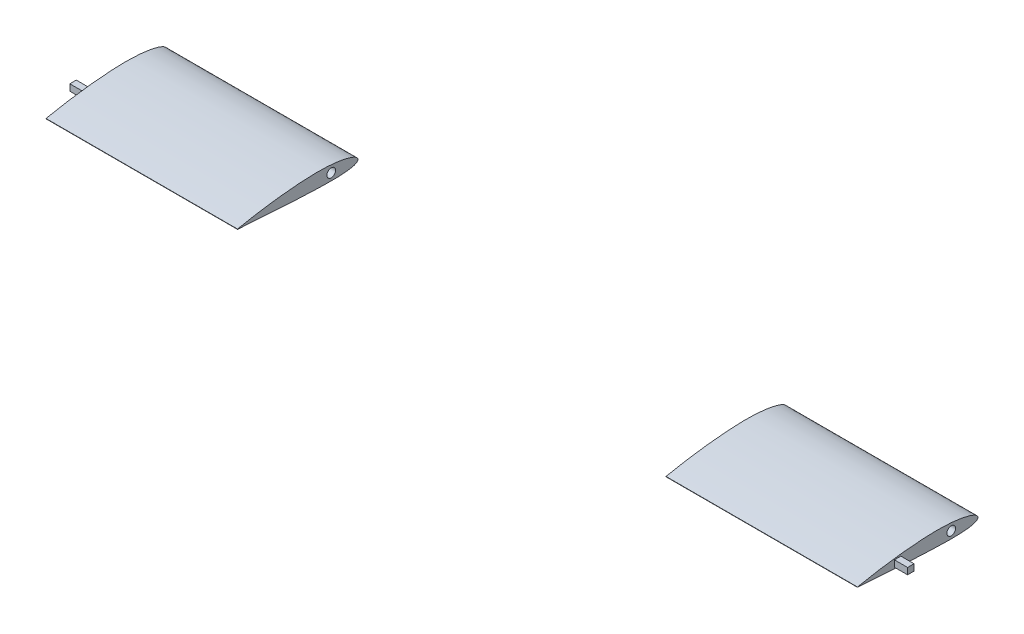
SolidWorks part; units mm, degrees
ref_plane "Front Plane" through (0, 0, 0) normal (0, 0, 1) x (1, 0, 0)
ref_plane "Top Plane" through (0, 0, 0) normal (0, 1, 0) x (1, 0, 0)
ref_plane "Right Plane" through (0, 0, 0) normal (1, 0, 0) x (0, 0, -1)
sketch "Sketch4" plane through (0, 0, 0) normal (0, 0, 1) x (1, 0, 0)
  line L0 (-30.3109, 17.5) -> (30.3109, 17.5)
  arc A1 (30.3109, 17.5) -> (-30.3109, 17.5) centre (0, 0) ccw
  dimension "D1" = 35
  dimension "D2" = 17.5
extrude "Exterior" add sketch "Sketch4" along normal blind 90 contours L0 A1
sketch "Sketch5" plane through (0, 0, 0) normal (0, 0, -1) x (-1, 0, 0)
  line L0 (30.3109, 17.5) -> (-30.3109, 17.5) construction
  line L1 (23.1247, 17.5) -> (-23.1247, 17.5)
  arc A0 (23.1247, 17.5) -> (-23.1247, 17.5) centre (0, 0) ccw
  dimension "D1" = 58
extrude "Boss-Extrude1" add sketch "Sketch5" along normal blind 15
curve "Curve3"
  spline degree 3 poles (0, 1.3, 1000) (0, 4.7133, 983.3426) (0, 11.531, 950.0715) (0, 24.0186, 883.4722) (0, 37.8548, 800.1781) (0, 52.175, 700.1592) (0, 64.1175, 600.1567) (0, 72.8619, 500.1109) (0, 78.7837, 400.0878) (0, 79.786, 316.6355) (0, 77.0249, 249.9395) (0, 72.979, 199.8766) (0, 66.5721, 149.7505) (0, 58.6825, 108.0331) (0, 49.7566, 74.7751) (0, 41.6416, 49.5609) (0, 32.1864, 28.1982) (0, 20.723, 9.771) (0, 0.8988, -6.2982) (0, -16.5264, 10.3934) (0, -24.4739, 28.476) (0, -30.5108, 49.7447) (0, -34.8393, 74.8759) (0, -38.5332, 108.2669) (0, -41.3764, 149.947) (0, -42.5163, 199.9941) (0, -42.3574, 250.0055) (0, -40.8857, 316.6783) (0, -38.2375, 400.0272) (0, -33.6287, 500.0334) (0, -27.6385, 600.0106) (0, -21.4122, 700.0048) (0, -15.1098, 800.0161) (0, -9.3053, 883.3314) (0, -4.8282, 950.0042) (0, -2.4761, 983.334) (0, -1.3, 1000) knots 0 0 0 0 0.025012 0.049959 0.099673 0.149206 0.198581 0.247805 0.296917 0.345953 0.370492 0.395091 0.419815 0.444799 0.45749 0.470406 0.483879 0.491264 0.503459 0.513609 0.520451 0.533235 0.545691 0.558032 0.582609 0.607135 0.631652 0.656174 0.705234 0.75432 0.803437 0.852566 0.901701 0.950849 0.975423 1 1 1 1
sketch "Sketch7" plane through (0, 0, 0) normal (1, 0, 0) x (0, 0, -1)
  line L0 (-90, 21.4324) -> (-90, 21.1984)
  line L1 (-90, 21.3154) -> (0, 21.434) construction
  line L2 (0, 21.434) -> (-0.0572, 64.8516) construction
  line L7 (-90, 17.5) -> (0, 17.5) construction
  line L9 (0, 17.5) -> (0, 29) construction
  spline S1 degree 3 poles (-90, 21.4324) (-88.5009, 21.7395) (-85.5067, 22.3531) (-79.5132, 23.4769) (-72.0173, 24.7221) (-63.0162, 26.0108) (-54.0165, 27.0856) (-45.013, 27.8725) (-36.0116, 28.4054) (-28.5014, 28.4956) (-22.4991, 28.2471) (-17.9938, 27.883) (-13.4827, 27.3065) (-9.7284, 26.5964) (-6.7354, 25.7932) (-4.4663, 25.0629) (-2.5438, 24.212) (-0.8854, 23.1803) (0.5607, 21.3963) (-0.9415, 19.8281) (-2.5688, 19.1129) (-4.4828, 18.5696) (-6.7445, 18.18) (-9.7495, 17.8476) (-13.5004, 17.5918) (-18.0044, 17.4892) (-22.5051, 17.5035) (-28.5052, 17.6359) (-36.0061, 17.8742) (-45.0061, 18.289) (-54.0034, 18.8281) (-63.0023, 19.3884) (-72.0027, 19.9556) (-79.5005, 20.478) (-85.5007, 20.8809) (-88.5002, 21.0925) (-90, 21.1984) knots 0 0 0 0 0.025012 0.049959 0.099673 0.149206 0.198581 0.247805 0.296917 0.345953 0.370492 0.395091 0.419815 0.444799 0.45749 0.470406 0.483879 0.491264 0.503459 0.513609 0.520451 0.533235 0.545691 0.558032 0.582609 0.607135 0.631652 0.656174 0.705234 0.75432 0.803437 0.852566 0.901701 0.950849 0.975423 1 1 1 1
  dimension "D1" = 90
ref_plane "Plane1" through (80, 0, 0) normal (1, 0, 0) x (0, 0, -1)
ref_plane "Plane2" through (-80, 0, 0) normal (1, 0, 0) x (0, 0, -1)
sketch "Sketch8" plane through (80, 0, 0) normal (1, 0, 0) x (0, 0, -1)
  line L0 (-90, 21.4324) -> (-90, 21.1984)
  spline S0 degree 3 poles (-716.115, 1915.3026) (-242.1094, -47.4437) (-166.1672, 7.229) (-79.5132, 23.4769) (-72.0173, 24.7221) (-63.0162, 26.0108) (-54.0165, 27.0856) (-45.013, 27.8725) (-36.0116, 28.4054) (-28.5014, 28.4956) (-22.4991, 28.2471) (-17.9938, 27.883) (-13.4827, 27.3065) (-9.7284, 26.5964) (-6.7354, 25.7932) (-4.4663, 25.0629) (-2.5438, 24.212) (-0.8854, 23.1803) (0.5607, 21.3963) (-0.9415, 19.8281) (-2.5688, 19.1129) (-4.4828, 18.5696) (-6.7445, 18.18) (-9.7495, 17.8476) (-13.5004, 17.5918) (-18.0044, 17.4892) (-22.5051, 17.5035) (-28.5052, 17.6359) (-36.0061, 17.8742) (-45.0061, 18.289) (-54.0034, 18.8281) (-63.0023, 19.3884) (-72.0027, 19.9556) (-79.5005, 20.478) (-222.3619, 30.0711) (-360.6967, 61.6518) (-633.8387, -1888.1939) knots -1.34139 -1.34139 -1.34139 -1.34139 0.025012 0.049959 0.099673 0.149206 0.198581 0.247805 0.296917 0.345953 0.370492 0.395091 0.419815 0.444799 0.45749 0.470406 0.483879 0.491264 0.503459 0.513609 0.520451 0.533235 0.545691 0.558032 0.582609 0.607135 0.631652 0.656174 0.705234 0.75432 0.803437 0.852566 0.901701 0.950849 0.975423 3.242166 3.242166 3.242166 3.242166 only from (-90, 21.4324) to (-90, 21.1984) construction
  spline S1 degree 3 poles (-90, 21.4324) (-88.5009, 21.7395) (-85.5067, 22.3531) (-79.5132, 23.4769) (-72.0173, 24.7221) (-63.0162, 26.0108) (-54.0165, 27.0856) (-45.013, 27.8725) (-36.0116, 28.4054) (-28.5014, 28.4956) (-22.4991, 28.2471) (-17.9938, 27.883) (-13.4827, 27.3065) (-9.7284, 26.5964) (-6.7354, 25.7932) (-4.4663, 25.0629) (-2.5438, 24.212) (-0.8854, 23.1803) (0.5607, 21.3963) (-0.9415, 19.8281) (-2.5688, 19.1129) (-4.4828, 18.5696) (-6.7445, 18.18) (-9.7495, 17.8476) (-13.5004, 17.5918) (-18.0044, 17.4892) (-22.5051, 17.5035) (-28.5052, 17.6359) (-36.0061, 17.8742) (-45.0061, 18.289) (-54.0034, 18.8281) (-63.0023, 19.3884) (-72.0027, 19.9556) (-79.5005, 20.478) (-85.5007, 20.8809) (-88.5002, 21.0925) (-90, 21.1984) knots 0 0 0 0 0.025012 0.049959 0.099673 0.149206 0.198581 0.247805 0.296917 0.345953 0.370492 0.395091 0.419815 0.444799 0.45749 0.470406 0.483879 0.491264 0.503459 0.513609 0.520451 0.533235 0.545691 0.558032 0.582609 0.607135 0.631652 0.656174 0.705234 0.75432 0.803437 0.852566 0.901701 0.950849 0.975423 1 1 1 1
sketch "Sketch9" plane through (-80, 0, 0) normal (1, 0, 0) x (0, 0, -1)
  line L0 (-90, 21.4324) -> (-90, 21.1984)
  spline S0 degree 3 poles (-716.115, 1915.3026) (-242.1094, -47.4437) (-166.1672, 7.229) (-79.5132, 23.4769) (-72.0173, 24.7221) (-63.0162, 26.0108) (-54.0165, 27.0856) (-45.013, 27.8725) (-36.0116, 28.4054) (-28.5014, 28.4956) (-22.4991, 28.2471) (-17.9938, 27.883) (-13.4827, 27.3065) (-9.7284, 26.5964) (-6.7354, 25.7932) (-4.4663, 25.0629) (-2.5438, 24.212) (-0.8854, 23.1803) (0.5607, 21.3963) (-0.9415, 19.8281) (-2.5688, 19.1129) (-4.4828, 18.5696) (-6.7445, 18.18) (-9.7495, 17.8476) (-13.5004, 17.5918) (-18.0044, 17.4892) (-22.5051, 17.5035) (-28.5052, 17.6359) (-36.0061, 17.8742) (-45.0061, 18.289) (-54.0034, 18.8281) (-63.0023, 19.3884) (-72.0027, 19.9556) (-79.5005, 20.478) (-222.3619, 30.0711) (-360.6967, 61.6518) (-633.8387, -1888.1939) knots -1.34139 -1.34139 -1.34139 -1.34139 0.025012 0.049959 0.099673 0.149206 0.198581 0.247805 0.296917 0.345953 0.370492 0.395091 0.419815 0.444799 0.45749 0.470406 0.483879 0.491264 0.503459 0.513609 0.520451 0.533235 0.545691 0.558032 0.582609 0.607135 0.631652 0.656174 0.705234 0.75432 0.803437 0.852566 0.901701 0.950849 0.975423 3.242166 3.242166 3.242166 3.242166 only from (-90, 21.4324) to (-90, 21.1984) construction
  spline S1 degree 3 poles (-90, 21.4324) (-88.5009, 21.7395) (-85.5067, 22.3531) (-79.5132, 23.4769) (-72.0173, 24.7221) (-63.0162, 26.0108) (-54.0165, 27.0856) (-45.013, 27.8725) (-36.0116, 28.4054) (-28.5014, 28.4956) (-22.4991, 28.2471) (-17.9938, 27.883) (-13.4827, 27.3065) (-9.7284, 26.5964) (-6.7354, 25.7932) (-4.4663, 25.0629) (-2.5438, 24.212) (-0.8854, 23.1803) (0.5607, 21.3963) (-0.9415, 19.8281) (-2.5688, 19.1129) (-4.4828, 18.5696) (-6.7445, 18.18) (-9.7495, 17.8476) (-13.5004, 17.5918) (-18.0044, 17.4892) (-22.5051, 17.5035) (-28.5052, 17.6359) (-36.0061, 17.8742) (-45.0061, 18.289) (-54.0034, 18.8281) (-63.0023, 19.3884) (-72.0027, 19.9556) (-79.5005, 20.478) (-85.5007, 20.8809) (-88.5002, 21.0925) (-90, 21.1984) knots 0 0 0 0 0.025012 0.049959 0.099673 0.149206 0.198581 0.247805 0.296917 0.345953 0.370492 0.395091 0.419815 0.444799 0.45749 0.470406 0.483879 0.491264 0.503459 0.513609 0.520451 0.533235 0.545691 0.558032 0.582609 0.607135 0.631652 0.656174 0.705234 0.75432 0.803437 0.852566 0.901701 0.950849 0.975423 1 1 1 1
loft "Loft9" add profiles "Sketch8", "Sketch9"
sketch "Sketch12" plane through (80, 0, 0) normal (1, 0, 0) x (0, 0, -1)
  line L0 (-90, 21.4324) -> (-90, 21.1984) construction
  line L1 (-90, 21.4324) -> (-90, 21.1984)
  line L2 (-90, 21.4324) -> (-97.2409, 26.9065)
  line L3 (-97.2409, 26.9065) -> (-90.2923, 42.7722)
  line L4 (-90.2923, 42.7722) -> (-30.1138, 44.0233)
  line L5 (-30.1138, 44.0233) -> (6.4186, 38.5184)
  line L6 (6.4186, 38.5184) -> (-0.0113, 30.0134)
  line L7 (0, 21.434) -> (-0.0572, 64.8516) construction
  line L8 (-0.0113, 30.0134) -> (-31.6288, 28.4362)
  spline S0 degree 3 poles (-716.115, 1915.3026) (-242.1094, -47.4437) (-166.1672, 7.229) (-79.5132, 23.4769) (-72.0173, 24.7221) (-63.0162, 26.0108) (-54.0165, 27.0856) (-45.013, 27.8725) (-36.0116, 28.4054) (-28.5014, 28.4956) (-22.4991, 28.2471) (-17.9938, 27.883) (-13.4827, 27.3065) (-9.7284, 26.5964) (-6.7354, 25.7932) (-4.4663, 25.0629) (-2.5438, 24.212) (-0.8854, 23.1803) (0.5607, 21.3963) (-0.9415, 19.8281) (-2.5688, 19.1129) (-4.4828, 18.5696) (-6.7445, 18.18) (-9.7495, 17.8476) (-13.5004, 17.5918) (-18.0044, 17.4892) (-22.5051, 17.5035) (-28.5052, 17.6359) (-36.0061, 17.8742) (-45.0061, 18.289) (-54.0034, 18.8281) (-63.0023, 19.3884) (-72.0027, 19.9556) (-79.5005, 20.478) (-222.3619, 30.0711) (-360.6967, 61.6518) (-633.8387, -1888.1939) knots -1.34139 -1.34139 -1.34139 -1.34139 0.025012 0.049959 0.099673 0.149206 0.198581 0.247805 0.296917 0.345953 0.370492 0.395091 0.419815 0.444799 0.45749 0.470406 0.483879 0.491264 0.503459 0.513609 0.520451 0.533235 0.545691 0.558032 0.582609 0.607135 0.631652 0.656174 0.705234 0.75432 0.803437 0.852566 0.901701 0.950849 0.975423 3.242166 3.242166 3.242166 3.242166 only from (-90, 21.4324) to (-90, 21.1984) construction
  spline S1 degree 3 poles (-90, 21.4324) (-88.5009, 21.7395) (-85.5067, 22.3531) (-79.5132, 23.4769) (-72.0173, 24.7221) (-63.0162, 26.0108) (-54.0165, 27.0856) (-45.013, 27.8725) (-37.5506, 28.3143) (-33.0875, 28.4219) (-31.6288, 28.4362) knots 0 0 0 0 0.025012 0.049959 0.099673 0.149206 0.198581 0.247805 0.296917 0.320756 0.320756 0.320756 0.320756
  spline S2 degree 3 poles (-90, 21.4324) (-88.518, 21.738) (-85.5578, 22.3484) (-79.6323, 23.4671) (-72.2211, 24.7077) (-63.3216, 25.9932) (-54.4234, 27.0671) (-45.5209, 27.8564) (-37.9232, 28.3157) (-33.2903, 28.4252) (-31.6288, 28.4362) knots 0 0 0 0 0.025012 0.049959 0.099673 0.149206 0.198581 0.247805 0.296917 0.324377 0.324377 0.324377 0.324377
extrude "Cut-Extrude1" cut sketch "Sketch12" against normal through all
ref_plane "Plane3" through (0, 30, 0) normal (0, 1, 0) x (1, 0, 0)
sketch "Sketch17" plane through (-80, 0, 0) normal (-1, 0, 0) x (0, 0, 1)
  line L0 (90, 21.4324) -> (90, 21.1984) construction
  line L1 (90, 21.4324) -> (90, 21.1984)
  spline S0 degree 3 poles (716.115, 1915.3026) (242.1094, -47.4437) (166.1672, 7.229) (79.5132, 23.4769) (72.0173, 24.7221) (63.0162, 26.0108) (54.0165, 27.0856) (45.013, 27.8725) (36.0116, 28.4054) (28.5014, 28.4956) (22.4991, 28.2471) (17.9938, 27.883) (13.4827, 27.3065) (9.7284, 26.5964) (6.7354, 25.7932) (4.4663, 25.0629) (2.5438, 24.212) (0.8854, 23.1803) (-0.5607, 21.3963) (0.9415, 19.8281) (2.5688, 19.1129) (4.4828, 18.5696) (6.7445, 18.18) (9.7495, 17.8476) (13.5004, 17.5918) (18.0044, 17.4892) (22.5051, 17.5035) (28.5052, 17.6359) (36.0061, 17.8742) (45.0061, 18.289) (54.0034, 18.8281) (63.0023, 19.3884) (72.0027, 19.9556) (79.5005, 20.478) (222.3619, 30.0711) (360.6967, 61.6518) (633.8387, -1888.1939) knots -1.34139 -1.34139 -1.34139 -1.34139 0.025012 0.049959 0.099673 0.149206 0.198581 0.247805 0.296917 0.345953 0.370492 0.395091 0.419815 0.444799 0.45749 0.470406 0.483879 0.491264 0.503459 0.513609 0.520451 0.533235 0.545691 0.558032 0.582609 0.607135 0.631652 0.656174 0.705234 0.75432 0.803437 0.852566 0.901701 0.950849 0.975423 3.242166 3.242166 3.242166 3.242166 only from (90, 21.4324) to (90, 21.1984) construction
  spline S1 degree 3 poles (90, 21.4324) (88.5009, 21.7395) (85.5067, 22.3531) (79.5132, 23.4769) (72.0173, 24.7221) (63.0162, 26.0108) (54.0165, 27.0856) (45.013, 27.8725) (36.0116, 28.4054) (28.5014, 28.4956) (22.4991, 28.2471) (17.9938, 27.883) (13.4827, 27.3065) (9.7284, 26.5964) (6.7354, 25.7932) (4.4663, 25.0629) (2.5438, 24.212) (0.8854, 23.1803) (-0.5607, 21.3963) (0.9415, 19.8281) (2.5688, 19.1129) (4.4828, 18.5696) (6.7445, 18.18) (9.7495, 17.8476) (13.5004, 17.5918) (18.0044, 17.4892) (22.5051, 17.5035) (28.5052, 17.6359) (36.0061, 17.8742) (45.0061, 18.289) (54.0034, 18.8281) (63.0023, 19.3884) (72.0027, 19.9556) (79.5005, 20.478) (85.5007, 20.8809) (88.5002, 21.0925) (90, 21.1984) knots 0 0 0 0 0.025012 0.049959 0.099673 0.149206 0.198581 0.247805 0.296917 0.345953 0.370492 0.395091 0.419815 0.444799 0.45749 0.470406 0.483879 0.491264 0.503459 0.513609 0.520451 0.533235 0.545691 0.558032 0.582609 0.607135 0.631652 0.656174 0.705234 0.75432 0.803437 0.852566 0.901701 0.950849 0.975423 1 1 1 1
extrude "Boss-Extrude2" add sketch "Sketch17" along normal blind 143
ref_plane "Plane5" through (-165, 0, 0) normal (1, 0, 0) x (0, 0, -1)
ref_plane "Plane6" through (-80, 0, 0) normal (1, 0, 0) x (0, 0, -1)
sketch "Sketch18" plane through (-80, 0, 0) normal (1, 0, 0) x (0, 0, -1)
  line L0 (-99.867, 5.7154) -> (-104.3901, 63.3258)
  line L1 (-104.3901, 63.3258) -> (31.8989, 60.8261)
  line L2 (31.8989, 60.8261) -> (39.2788, -3.2119)
  line L3 (39.2788, -3.2119) -> (-99.867, 5.7154)
extrude "Cut-Extrude6" cut sketch "Sketch18" along normal through all
sketch "Sketch13" plane through (-80, 0, 0) normal (-1, 0, 0) x (0, 0, 1)
  line L0 (20, 17.5001) -> (20, 28.0366) construction
  circle A0 centre (20, 22.7683) radius 3.25
  spline S0 degree 3 poles (90, 21.4324) (88.5009, 21.7395) (85.5067, 22.3531) (79.5132, 23.4769) (72.0173, 24.7221) (63.0162, 26.0108) (54.0165, 27.0856) (45.013, 27.8725) (36.0116, 28.4054) (28.5014, 28.4956) (22.4991, 28.2471) (17.9938, 27.883) (13.4827, 27.3065) (9.7284, 26.5964) (6.7354, 25.7932) (4.4663, 25.0629) (2.5438, 24.212) (0.8854, 23.1803) (-0.5607, 21.3963) (0.9415, 19.8281) (2.5688, 19.1129) (4.4828, 18.5696) (6.7445, 18.18) (9.7495, 17.8476) (13.5004, 17.5918) (18.0044, 17.4892) (22.5051, 17.5035) (28.5052, 17.6359) (36.0061, 17.8742) (45.0061, 18.289) (54.0034, 18.8281) (63.0023, 19.3884) (72.0027, 19.9556) (79.5005, 20.478) (85.5007, 20.8809) (88.5002, 21.0925) (90, 21.1984) knots 0 0 0 0 0.025012 0.049959 0.099673 0.149206 0.198581 0.247805 0.296917 0.345953 0.370492 0.395091 0.419815 0.444799 0.45749 0.470406 0.483879 0.491264 0.503459 0.513609 0.520451 0.533235 0.545691 0.558032 0.582609 0.607135 0.631652 0.656174 0.705234 0.75432 0.803437 0.852566 0.901701 0.950849 0.975423 1 1 1 1 construction
  point P8 (20, 22.7683)
  dimension "D1" = 6.5
  dimension "D2" = 20
extrude "Cut-Extrude2" cut sketch "Sketch13" against normal through all and the other way through all
sketch "Sketch19" plane through (-223, 0, 0) normal (-1, 0, 0) x (0, 0, 1)
  line L0 (57.6, 25.1683) -> (62.4, 25.1683)
  line L1 (62.4, 25.1683) -> (62.4, 20.3683)
  line L2 (62.4, 20.3683) -> (57.6, 20.3683)
  line L3 (57.6, 20.3683) -> (57.6, 25.1683)
  line L4 (20, 22.7683) -> (28.325, 22.7683) construction
  circle A0 centre (20, 22.7683) radius 3.25 construction
  point P6 (60, 25.1683)
  point P10 (0, 0)
  point P11 (57.6, 22.7683)
  dimension "D3" = 40
  dimension "D1" = 4.8
  dimension "D2" = 4.8
extrude "Boss-Extrude3" add sketch "Sketch19" along normal blind 9.8
mirror "Mirror3" about plane through (80, 0, 0) normal (1, 0, 0)
equation "\"fuse_diam\"= 0.07"
equation "\"fuse_rad\"= 0.035"
equation "\"battery_length\"= 0.076"
equation "\"battery_width\"= 0.034"
equation "\"battery_height\"= 0.051"
equation "\"bat_bay_length\"= 0.096"
equation "\"shell\"= 0.002"
equation "\"D1@Exterior\"=\"chord_length\""
equation "\"wing_shelf\"= 0.0175"
equation "\"chord_length\"= 0.09"
equation "\"tail_length\"= 0.26598000000000005"
equation "\"tail_diam\"= 0.035"
equation "\"connector\"= 0.06649500000000001"
equation "\"D2@Sketch4\"=\"wing_shelf\""
equation "\"D1@Sketch4\"=\"fuse_rad\""
equation "\"D1@Sketch5\"=\"fuse_diam\"-0.012"
equation "\"D1@Sketch7\"=\"chord_length\""
